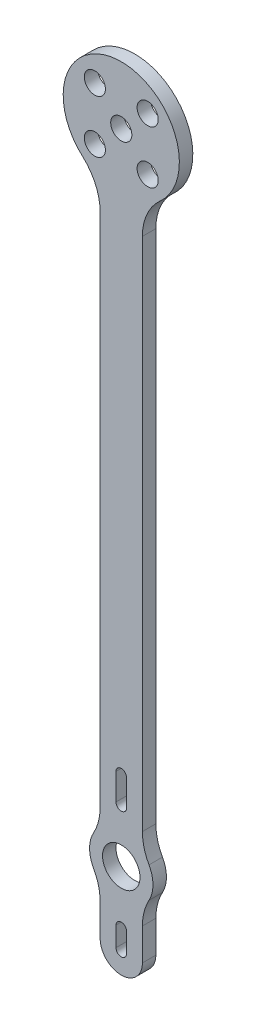
SolidWorks part; units mm, degrees
ref_plane "Front Plane" through (0, 0, 0) normal (0, 0, 1) x (1, 0, 0)
ref_plane "Top Plane" through (0, 0, 0) normal (0, 1, 0) x (1, 0, 0)
ref_plane "Right Plane" through (0, 0, 0) normal (1, 0, 0) x (0, 0, -1)
sketch "Model" plane through (0, 0, 0) normal (0, 0, 1) x (1, 0, 0)
  line L0 (-1, 18.4215) -> (-1, -3.4062) construction
  line L1 (1, 18.4215) -> (1, 5.9161) construction
  line L7 (-7.5978, 10.1) -> (4.5933, 10.1) construction
  line L8 (-1.9126, -10.1) -> (1, -10.1) construction
  line L9 (-3.5953, 15.1) -> (3.0222, 15.1) construction
  line L10 (-2.3019, -13.8) -> (3.0222, -13.8) construction
  line L11 (-4, 105.3475) -> (-4, 7.746)
  line L12 (4, 105.3475) -> (4, 7.746)
  line L13 (-1, -10.1) -> (-1, -13.8)
  line L14 (1, -10.1) -> (1, -13.8)
  line L15 (-1, 15.1) -> (-1, 10.1)
  line L16 (1, 15.1) -> (1, 10.1)
  line L17 (1, 3.4062) -> (1, -5.9161) construction
  line L18 (1, -10.1) -> (1, -18.7667) construction
  line L19 (-1, -5.9161) -> (-1, -18.7667) construction
  line L20 (-4, -7.746) -> (-4, -13.8)
  line L21 (4, -7.746) -> (4, -13.8)
  circle A0 centre (0, 0) radius 3.55
  arc A1 (-5.25, 2.9047) -> (-5.25, -2.9047) centre (0, 0) ccw
  arc A2 (1, 15.1) -> (-1, 15.1) centre (0, 15.1) ccw
  arc A3 (-1, 10.1) -> (1, 10.1) centre (0, 10.1) ccw
  arc A4 (1, -10.1) -> (-1, -10.1) centre (0, -10.1) ccw
  arc A5 (-1, -13.8) -> (1, -13.8) centre (0, -13.8) ccw
  circle A6 centre (0, 121) radius 2
  circle A7 centre (-5, 126) radius 2
  arc A8 (-4, -13.8) -> (4, -13.8) centre (0, -13.8) ccw
  arc A9 (5.25, -2.9047) -> (5.25, 2.9047) centre (0, 0) ccw
  arc A10 (4, 7.746) -> (5.25, 2.9047) centre (14, 7.746) ccw
  arc A11 (5.25, -2.9047) -> (4, -7.746) centre (14, -7.746) ccw
  arc A12 (-5.25, -2.9047) -> (-4, -7.746) centre (-14, -7.746) cw
  arc A13 (-5.25, 2.9047) -> (-4, 7.746) centre (-14, 7.746) ccw
  arc A14 (7.3333, 112.8011) -> (-7.3333, 112.8011) centre (0, 121) ccw
  circle A15 centre (5, 126) radius 2
  circle A16 centre (5, 116) radius 2
  circle A17 centre (-5, 116) radius 2
  arc A18 (4, 105.3475) -> (7.3333, 112.8011) centre (14, 105.3475) cw
  arc A19 (-4, 105.3475) -> (-7.3333, 112.8011) centre (-14, 105.3475) ccw
  point P44 (4, -4.4721)
  point P47 (-4, -4.4721)
  dimension "D1" = 7.1
  dimension "D2" = 12
  dimension "D15" = 4
  dimension "D5" = 10
  dimension "D6" = 22
  dimension "D7" = 4
  dimension "D20" = 10
  dimension "D3" = 1
  dimension "D4" = 1
  dimension "D8" = 5
  dimension "D9" = 10.1
  dimension "D10" = 10.1
  dimension "D11" = 3.7
  dimension "D12" = 5
  dimension "D13" = 4
  dimension "D14" = 4
  dimension "D16" = 121
  dimension "D17" = 5
  dimension "D18" = 2
  dimension "D19" = 2
extrude "Boss-Extrude1" add sketch "Model" along normal blind 2.55
